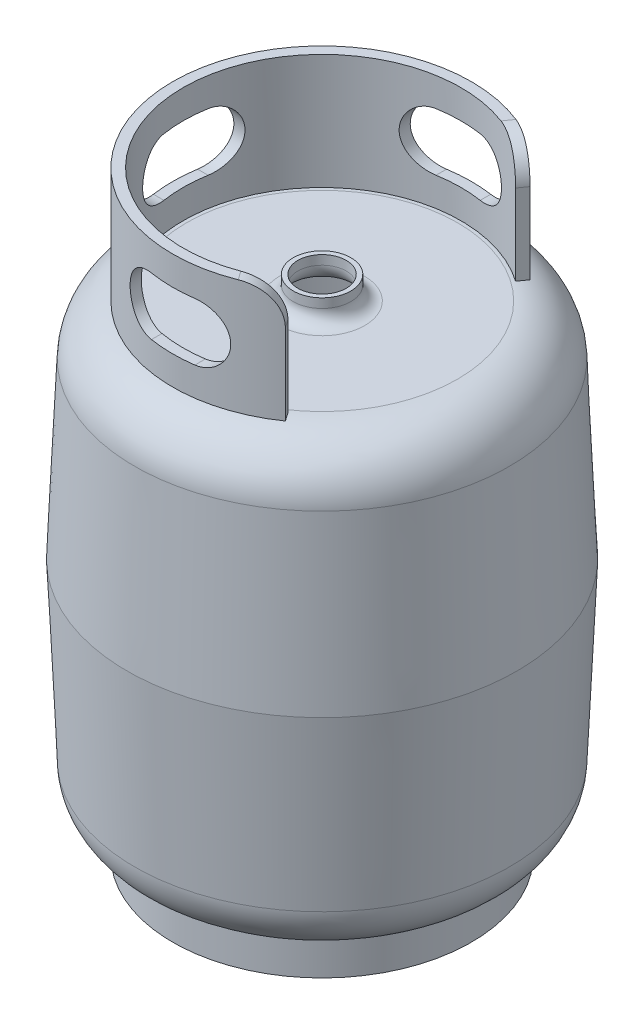
SolidWorks part; units mm, degrees
material "1060 Alloy"
ref_plane "Front Plane" through (0, 0, 0) normal (0, 0, 1) x (1, 0, 0)
ref_plane "Top Plane" through (0, 0, 0) normal (0, 1, 0) x (1, 0, 0)
ref_plane "Right Plane" through (0, 0, 0) normal (1, 0, 0) x (0, 0, -1)
sketch "Sketch1" plane through (0, 0, 0) normal (0, 0, 1) x (1, 0, 0)
  line L0 (0, 0) -> (0, 213.5) construction
  line L1 (0, 213.5) -> (25, 213.5) construction
  line L2 (25, 213.5) -> (25, 205.5)
  line L3 (37, 193.5) -> (117.5428, 193.5)
  line L4 (162.5, 150.4629) -> (169.0694, 0)
  line L5 (169.0694, 0) -> (162.5, -150.4629)
  line L6 (117.5428, -193.5) -> (0, -193.5)
  line L7 (0, 0) -> (0, -193.5) construction
  line L8 (0, 0) -> (169.0694, 0) construction
  line L9 (21, 209.5) -> (21, 213.5)
  line L10 (21, 209.5) -> (21, 205.5)
  line L11 (37, 189.5) -> (117.5428, 189.5)
  line L12 (158.5038, 150.2884) -> (165.0655, 0)
  line L13 (165.0655, 0) -> (158.5038, -150.2884)
  line L14 (117.5428, -189.5) -> (0, -189.5)
  line L15 (0, 209.5) -> (21, 209.5) construction
  line L16 (21, 213.5) -> (25, 213.5)
  line L17 (0, -189.5) -> (0, -193.5)
  arc A0 (25, 205.5) -> (37, 193.5) centre (37, 205.5) ccw
  arc A1 (117.5428, 193.5) -> (162.5, 150.4629) centre (117.5428, 148.5) cw
  arc A2 (162.5, -150.4629) -> (117.5428, -193.5) centre (117.5428, -148.5) cw
  arc A3 (21, 205.5) -> (37, 189.5) centre (37, 205.5) ccw
  arc A4 (117.5428, 189.5) -> (158.5038, 150.2884) centre (117.5428, 148.5) cw
  arc A5 (158.5038, -150.2884) -> (117.5428, -189.5) centre (117.5428, -148.5) cw
  dimension "D2" = 12
  dimension "D3" = 45
  dimension "D4" = 45
  dimension "D1" = 387
  dimension "D5" = 92.5
  dimension "D6" = 92.5
  dimension "D7" = 50
  dimension "D8" = 20
  dimension "D9" = 325
  dimension "D10" = 4
revolve "Revolve1" add sketch "Sketch1" angle 360 about L0
sketch "Sketch2" plane through (0, 193.5, 0) normal (0, 1, 0) x (1, 0, 0)
  line L0 (0, 0) -> (129.5428, 0) construction
  line L1 (0, 0) -> (74.3027, 106.1153) construction
  line L2 (74.3027, 106.1153) -> (0, 0) construction
  line L3 (0, 0) -> (74.3027, -106.1153) construction
  line L4 (74.3027, 106.1153) -> (69.1405, 98.7429)
  line L5 (69.1405, -98.7429) -> (74.3027, -106.1153)
  circle A2 centre (0, 0) radius 120.5428
  arc A3 (69.1405, 98.7429) -> (69.1405, -98.7429) centre (0, 0) ccw
  circle A5 centre (0, 0) radius 129.5428
  arc A6 (74.3027, 106.1153) -> (74.3027, -106.1153) centre (0, 0) ccw
  dimension "D3" = 55
  dimension "D4" = 55
  dimension "D1" = 3
  dimension "D2" = 12
extrude "Boss-Extrude1" add sketch "Sketch2" along normal blind 100 separate body
sketch "Sketch3" plane through (0, 0, 0) normal (0, 0, 1) x (1, 0, 0)
  line L0 (-20, 243.5) -> (18, 243.5) construction
  line L1 (-20, 268.5) -> (18, 268.5)
  line L2 (-20, 218.5) -> (18, 218.5)
  line L3 (69.1405, 293.5) -> (-120.5428, 293.5) construction
  arc A0 (-20, 268.5) -> (-20, 218.5) centre (-20, 243.5) ccw
  arc A1 (18, 218.5) -> (18, 268.5) centre (18, 243.5) ccw
  point P2 (-1, 243.5)
  dimension "D3" = 25
  dimension "D1" = 18
  dimension "D2" = 38
  dimension "D4" = 50
extrude "Cut-Extrude1" cut sketch "Sketch3" against normal through all both and the other way through all
fillet "Fillet1" radius 30 1 edges at (71.7216, 293.5, 102.4291)
fillet "Fillet2" radius 30 1 edges at (71.7216, 293.5, -102.4291)
sketch "Sketch4" plane through (0, 0, 0) normal (1, 0, 0) x (0, 0, -1)
  line L0 (20, 243.5) -> (-18, 243.5) construction
  line L1 (20, 218.5) -> (-18, 218.5)
  line L2 (20, 268.5) -> (-18, 268.5)
  line L3 (129.5428, 293.5) -> (-129.5428, 293.5) construction
  arc A0 (20, 218.5) -> (20, 268.5) centre (20, 243.5) ccw
  arc A1 (-18, 268.5) -> (-18, 218.5) centre (-18, 243.5) ccw
  point P2 (1, 243.5)
  dimension "D2" = 25
  dimension "D1" = 18
  dimension "D3" = 38
  dimension "D4" = 50
extrude "Cut-Extrude2" cut sketch "Sketch4" against normal through all and the other way through all
sketch "Sketch6" plane through (0, -193.5, 0) normal (0, -1, 0) x (1, 0, 0)
  circle A2 centre (0, 0) radius 120.5428
  circle A3 centre (0, 0) radius 120.5428
  circle A5 centre (0, 0) radius 129.5428
  circle A6 centre (0, 0) radius 129.5428
  dimension "D1" = 3
  dimension "D2" = 12
extrude "Boss-Extrude3" add sketch "Sketch6" along normal blind 30 separate body
equation "\"A\"= 325"
equation "\"B\"= 387"
